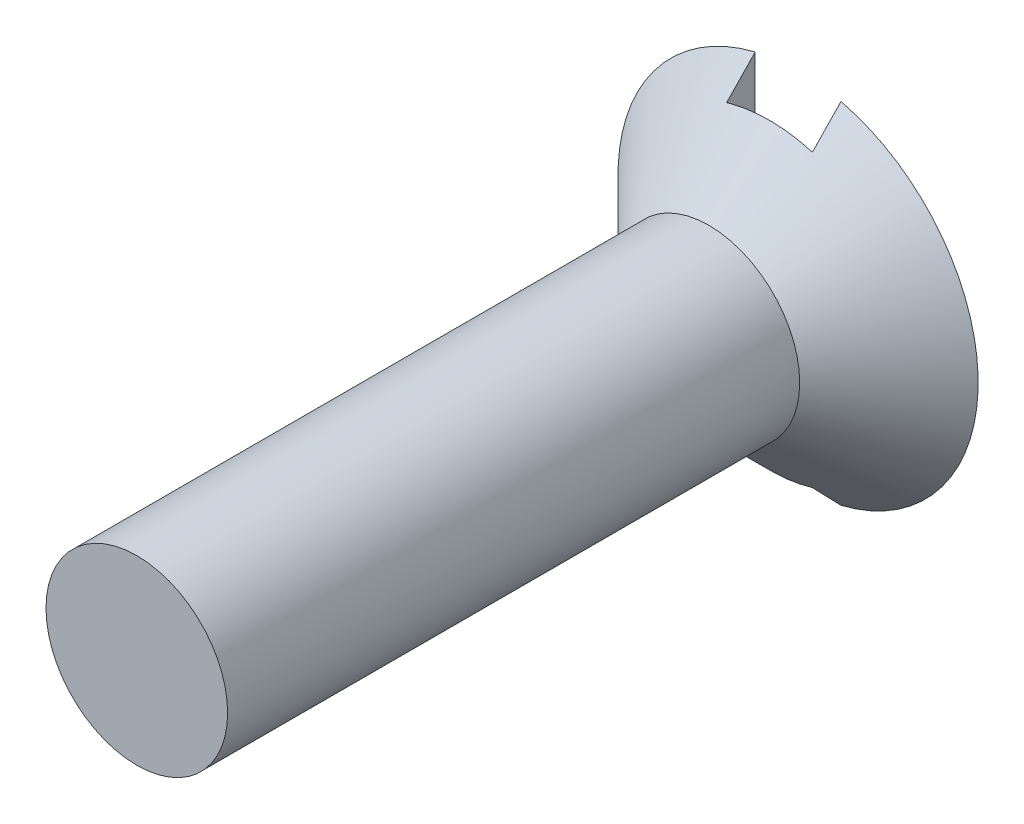
SolidWorks part; units mm, degrees
ref_plane "Plano frontal" through (0, 0, 0) normal (0, 0, 1) x (1, 0, 0)
ref_plane "Plano superior" through (0, 0, 0) normal (0, 1, 0) x (1, 0, 0)
ref_plane "Plano direito" through (0, 0, 0) normal (1, 0, 0) x (0, 0, -1)
sketch "Esboço1" plane through (0, 0, 0) normal (1, 0, 0) x (0, 0, -1)
  line L0 (0, 0) -> (0, 3.1475)
  line L1 (0, 3.1475) -> (-1.56, 1.5875)
  line L2 (-1.56, 1.5875) -> (-11.56, 1.5875)
  line L3 (-11.56, 1.5875) -> (-11.56, 0)
  line L4 (-11.56, 0) -> (0, 0) construction
  line L5 (0, 0) -> (-11.56, 0)
  dimension "D1" = 1.5875
  dimension "D2" = 10
  dimension "D3" = 1.56
  dimension "D4" = 45
revolve "Revolução1" add sketch "Esboço1" angle 360 about L4
sketch "Esboço2" plane through (0, 0, 0) normal (0, 0, -1) x (-1, 0, 0)
  line L1 (-0.75, 3.5) -> (0.75, 3.5)
  line L2 (-0.75, 3.5) -> (-0.75, -3.5)
  line L3 (-0.75, -3.5) -> (0.75, -3.5)
  line L4 (0.75, 3.5) -> (0.75, -3.5)
  line L5 (-0.75, 3.5) -> (0.75, -3.5) construction
  line L6 (-0.75, -3.5) -> (0.75, 3.5) construction
  point P0 (0, 0)
  dimension "D1" = 7
  dimension "D2" = 1.5
extrude "Corte-extrusão1" cut sketch "Esboço2" against normal blind 0.5
